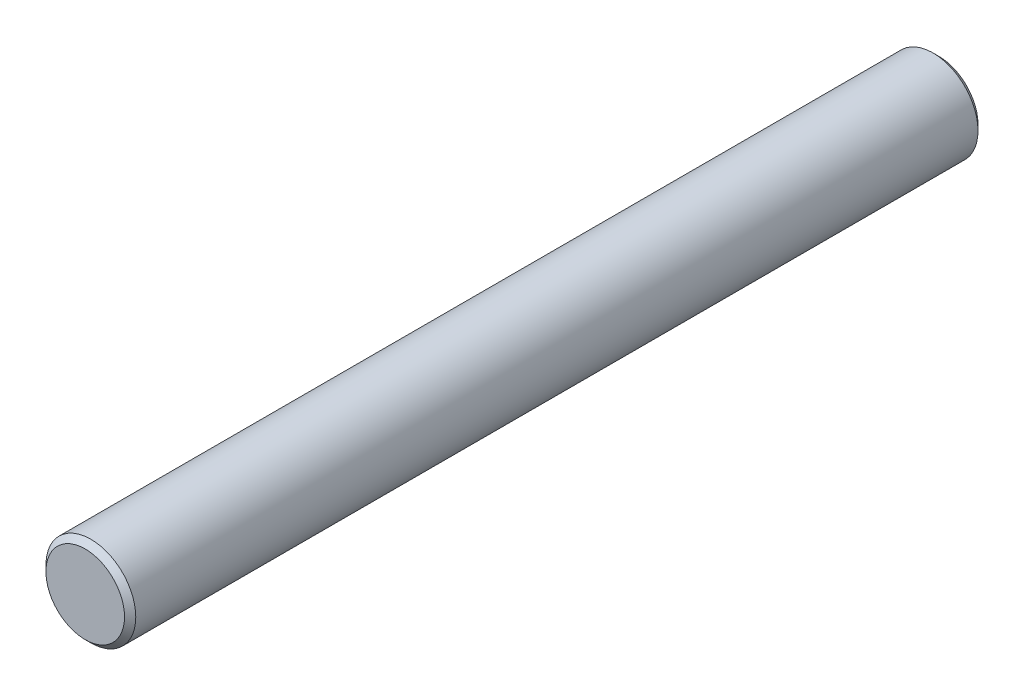
SolidWorks part; units mm, degrees
material "Plain Carbon Steel"
ref_plane "Front Plane" through (0, 0, 0) normal (0, 0, 1) x (1, 0, 0)
ref_plane "Top Plane" through (0, 0, 0) normal (0, 1, 0) x (1, 0, 0)
ref_plane "Right Plane" through (0, 0, 0) normal (1, 0, 0) x (0, 0, -1)
sketch "Sketch1" plane through (0, 0, 0) normal (0, 0, 1) x (1, 0, 0)
  circle A0 centre (0, 0) radius 4
  dimension "D1" = 8
extrude "Boss-Extrude1" add sketch "Sketch1" along normal blind 76
chamfer "Chamfer1" distance 0.5 angle 45 2 edges at (4, 0, 0) (4, 0, 76)
